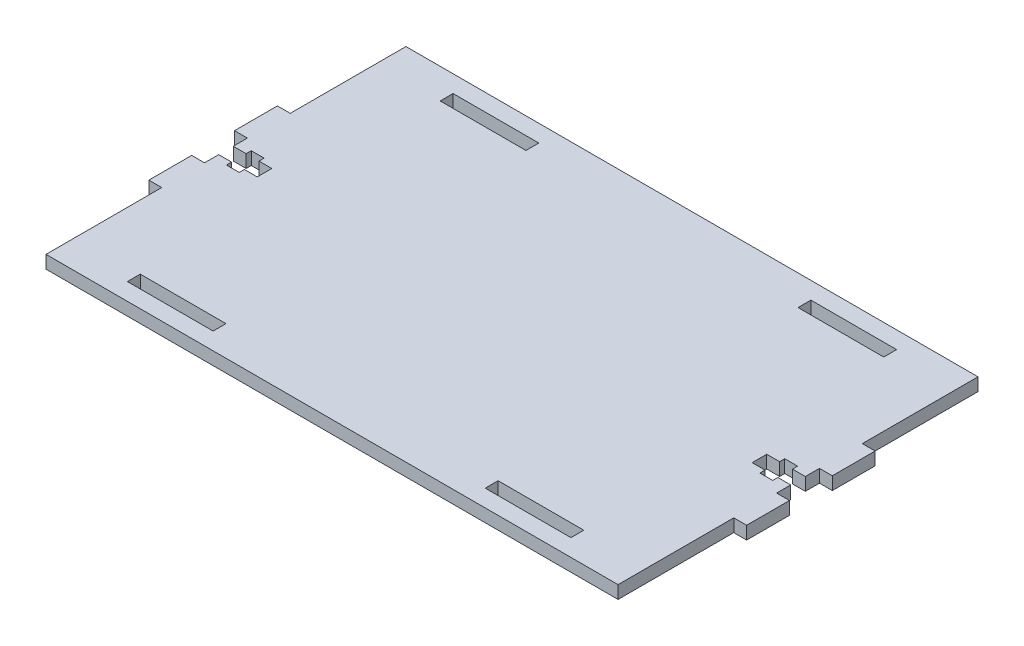
SolidWorks part; units mm, degrees
ref_plane "Спереди" through (0, 0, 0) normal (0, 0, 1) x (1, 0, 0)
ref_plane "Сверху" through (0, 0, 0) normal (0, 1, 0) x (1, 0, 0)
ref_plane "Справа" through (0, 0, 0) normal (1, 0, 0) x (0, 0, -1)
sketch "Sketch1" plane through (0, 0, 0) normal (0, 1, 0) x (1, 0, 0)
  line L0 (53.8429, -48.0568) -> (-9.6571, -48.0568) construction
  line L1 (-44.6571, 31.9432) -> (88.8429, 31.9432)
  line L2 (-44.6571, 31.9432) -> (-44.6571, -52.0568)
  line L3 (-44.6571, -52.0568) -> (88.8429, -52.0568)
  line L4 (88.8429, 31.9432) -> (88.8429, -52.0568)
  line L5 (88.8429, 27.9432) -> (88.8429, 24.9432) construction
  dimension "D1" = 4
extrude "Boss-Extrude1" add sketch "Sketch1" along normal blind 3
sketch "Sketch2" plane through (0, 0, 0) normal (0, -1, 0) x (1, 0, 0)
  line L0 (53.8429, 45.0568) -> (73.8429, 45.0568) construction
  line L1 (73.8429, 45.0568) -> (73.8429, 48.0568) construction
  line L2 (73.8429, 48.0568) -> (53.8429, 48.0568) construction
  line L3 (53.8429, 48.0568) -> (53.8429, 45.0568) construction
  line L4 (-29.6571, 45.0568) -> (-9.6571, 45.0568) construction
  line L5 (-9.6571, 45.0568) -> (-9.6571, 48.0568) construction
  line L6 (-9.6571, 48.0568) -> (-29.6571, 48.0568) construction
  line L7 (-29.6571, 48.0568) -> (-29.6571, 45.0568) construction
  line L8 (-29.6571, -27.9432) -> (-9.6571, -27.9432) construction
  line L9 (-9.6571, -27.9432) -> (-9.6571, -24.9432) construction
  line L10 (-9.6571, -24.9432) -> (-29.6571, -24.9432) construction
  line L11 (-29.6571, -24.9432) -> (-29.6571, -27.9432) construction
  line L12 (53.8429, -27.9432) -> (73.8429, -27.9432) construction
  line L13 (73.8429, -27.9432) -> (73.8429, -24.9432) construction
  line L14 (73.8429, -24.9432) -> (53.8429, -24.9432) construction
  line L15 (53.8429, -24.9432) -> (53.8429, -27.9432) construction
  line L16 (53.8429, 45.0568) -> (73.8429, 45.0568)
  line L17 (73.8429, 45.0568) -> (73.8429, 48.0568)
  line L18 (73.8429, 48.0568) -> (53.8429, 48.0568)
  line L19 (53.8429, 48.0568) -> (53.8429, 45.0568)
  line L20 (-29.6571, 45.0568) -> (-9.6571, 45.0568)
  line L21 (-9.6571, 45.0568) -> (-9.6571, 48.0568)
  line L22 (-9.6571, 48.0568) -> (-29.6571, 48.0568)
  line L23 (-29.6571, 48.0568) -> (-29.6571, 45.0568)
  line L24 (-29.6571, -27.9432) -> (-9.6571, -27.9432)
  line L25 (-9.6571, -27.9432) -> (-9.6571, -24.9432)
  line L26 (-9.6571, -24.9432) -> (-29.6571, -24.9432)
  line L27 (-29.6571, -24.9432) -> (-29.6571, -27.9432)
  line L28 (53.8429, -27.9432) -> (73.8429, -27.9432)
  line L29 (73.8429, -27.9432) -> (73.8429, -24.9432)
  line L30 (73.8429, -24.9432) -> (53.8429, -24.9432)
  line L31 (53.8429, -24.9432) -> (53.8429, -27.9432)
extrude "Cut-Extrude1" cut sketch "Sketch2" against normal through all
sketch "Sketch3" plane through (0, 0, 0) normal (0, -1, 0) x (1, 0, 0)
  line L0 (-44.6571, -31.9432) -> (-44.6571, 52.0568) construction
  line L1 (91.8429, -4.9432) -> (88.8429, -4.9432)
  line L2 (91.8429, -4.9432) -> (91.8429, 25.0568)
  line L3 (91.8429, 25.0568) -> (88.8429, 25.0568)
  line L4 (88.8429, -4.9432) -> (88.8429, 25.0568)
  line L5 (91.8429, -4.9432) -> (88.8429, 25.0568) construction
  line L6 (91.8429, 25.0568) -> (88.8429, -4.9432) construction
  line L7 (-44.6571, -4.9432) -> (-47.6571, -4.9432)
  line L8 (-44.6571, -4.9432) -> (-44.6571, 25.0568)
  line L9 (-44.6571, 25.0568) -> (-47.6571, 25.0568)
  line L10 (-47.6571, -4.9432) -> (-47.6571, 25.0568)
  line L11 (-44.6571, -4.9432) -> (-47.6571, 25.0568) construction
  line L12 (-44.6571, 25.0568) -> (-47.6571, -4.9432) construction
  line L13 (88.8429, 52.0568) -> (88.8429, -31.9432) construction
  point P0 (90.3429, 10.0568)
  point P5 (-46.1571, 10.0568)
  point P13 (-44.6571, 10.0568)
  dimension "D1" = 3
  dimension "D2" = 30
extrude "Boss-Extrude2" add sketch "Sketch3" against normal through all
sketch "Sketch4" plane through (0, 0, 0) normal (0, -1, 0) x (1, 0, 0)
  line L0 (88.8429, 5.0568) -> (94.8429, 5.0568)
  line L1 (88.8429, 5.0568) -> (88.8429, 15.0568)
  line L2 (88.8429, 15.0568) -> (94.8429, 15.0568)
  line L3 (94.8429, 5.0568) -> (94.8429, 15.0568)
  line L4 (88.8429, 5.0568) -> (94.8429, 15.0568) construction
  line L5 (88.8429, 15.0568) -> (94.8429, 5.0568) construction
  line L6 (88.8429, 8.3568) -> (85.8429, 8.3568)
  line L7 (88.8429, 8.3568) -> (88.8429, 11.7568)
  line L8 (88.8429, 11.7568) -> (85.8429, 11.7568)
  line L9 (85.8429, 8.3568) -> (85.8429, 11.7568)
  line L10 (88.8429, 8.3568) -> (85.8429, 11.7568) construction
  line L11 (88.8429, 11.7568) -> (85.8429, 8.3568) construction
  line L12 (85.8429, 7.1568) -> (82.8429, 7.1568)
  line L13 (85.8429, 7.1568) -> (85.8429, 12.9568)
  line L14 (85.8429, 12.9568) -> (82.8429, 12.9568)
  line L15 (82.8429, 7.1568) -> (82.8429, 12.9568)
  line L16 (85.8429, 7.1568) -> (82.8429, 12.9568) construction
  line L17 (85.8429, 12.9568) -> (82.8429, 7.1568) construction
  line L18 (88.8429, -4.9432) -> (88.8429, -31.9432) construction
  line L19 (91.8429, -4.9432) -> (91.8429, 25.0568) construction
  line L21 (79.8429, 11.7568) -> (82.8429, 11.7568)
  line L22 (79.8429, 11.7568) -> (79.8429, 8.3568)
  line L23 (79.8429, 8.3568) -> (82.8429, 8.3568)
  line L24 (82.8429, 11.7568) -> (82.8429, 8.3568)
  line L25 (79.8429, 11.7568) -> (82.8429, 8.3568) construction
  line L26 (79.8429, 8.3568) -> (82.8429, 11.7568) construction
  point P0 (91.8429, 10.0568)
  point P5 (87.3429, 10.0568)
  point P10 (84.3429, 10.0568)
  point P17 (81.3429, 10.0568)
  point P21 (91.8429, 10.0568)
  line M33 (91.8429, -4.9432) -> (91.8429, 25.0568)
  dimension "D1" = 10
  dimension "D2" = 3.4
  dimension "D3" = 3
  dimension "D4" = 3
  dimension "D5" = 5.8
extrude "Cut-Extrude2" cut sketch "Sketch4" against normal through all both and the other way through all contours L2 L1 L0 M33 | L9 L6 L1 L8 | L15 L12 L13 L9 L14 | L22 L23 L15 L21
sketch "Sketch5" plane through (0, 0, 0) normal (0, -1, 0) x (1, 0, 0)
  line L0 (-44.6571, 52.0568) -> (88.8429, -31.9432) construction
  line L1 (-44.6571, -31.9432) -> (88.8429, 52.0568) construction
  point P8 (22.0929, 10.0568)
ref_plane "Plane1" through (22.0929, 0, 0) normal (1, 0, 0) x (0, 0, -1)
mirror "Mirror1" about plane through (22.0929, 0, 0) normal (1, 0, 0) of "Cut-Extrude2"
